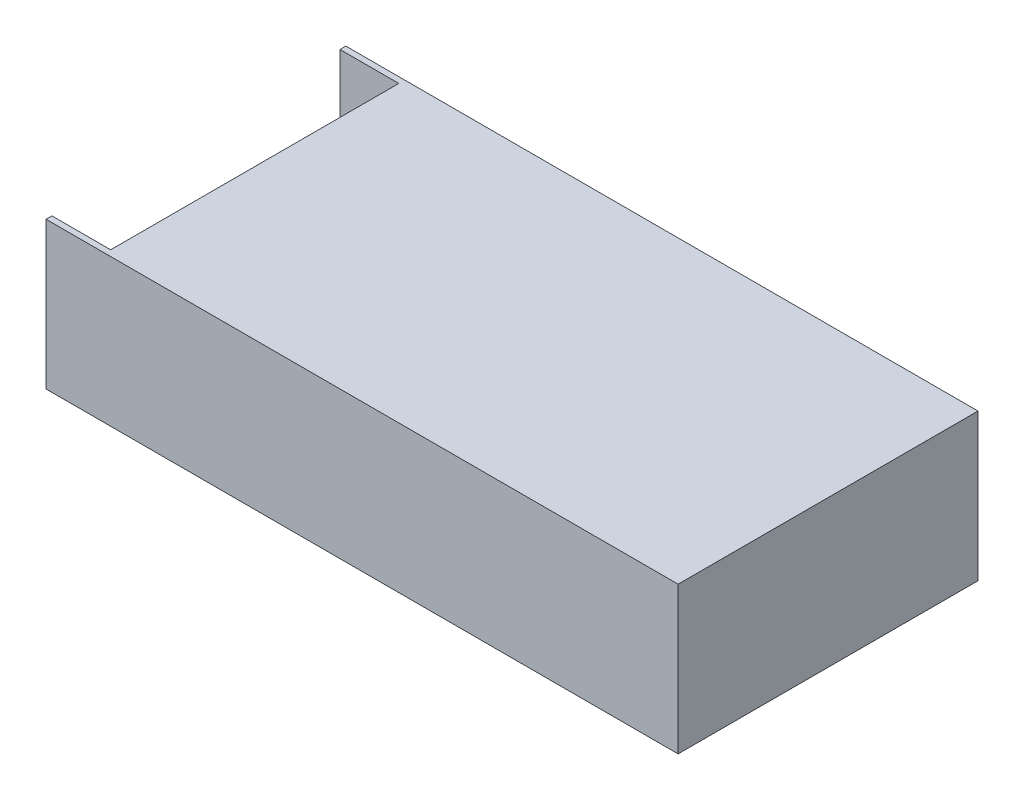
SolidWorks part; units mm, degrees
ref_plane "Front Plane" through (0, 0, 0) normal (0, 0, 1) x (1, 0, 0)
ref_plane "Top Plane" through (0, 0, 0) normal (0, 1, 0) x (1, 0, 0)
ref_plane "Right Plane" through (0, 0, 0) normal (1, 0, 0) x (0, 0, -1)
sketch "Sketch1" plane through (0, 0, 0) normal (0, 1, 0) x (1, 0, 0)
  line L1 (0, 0) -> (215, 0)
  line L2 (0, 0) -> (0, 102)
  line L3 (0, 102) -> (215, 102)
  line L4 (215, 0) -> (215, 102)
  dimension "D1" = 215
  dimension "D2" = 102
extrude "Boss-Extrude1" add sketch "Sketch1" along normal blind 50
sketch "Sketch2" plane through (0, 50, 0) normal (0, 1, 0) x (1, 0, 0)
  line L0 (0, 102) -> (0, 0) construction
  line L1 (0, 100) -> (20, 100)
  line L2 (0, 100) -> (0, 2)
  line L3 (0, 2) -> (20, 2)
  line L4 (20, 100) -> (20, 2)
  line L5 (215, 0) -> (215, 102) construction
  line L6 (0, 0) -> (215, 0) construction
  line L7 (215, 102) -> (0, 102) construction
  dimension "D1" = 195
  dimension "D2" = 2
  dimension "D3" = 2
extrude "Cut-Extrude1" cut sketch "Sketch2" against normal blind 25
